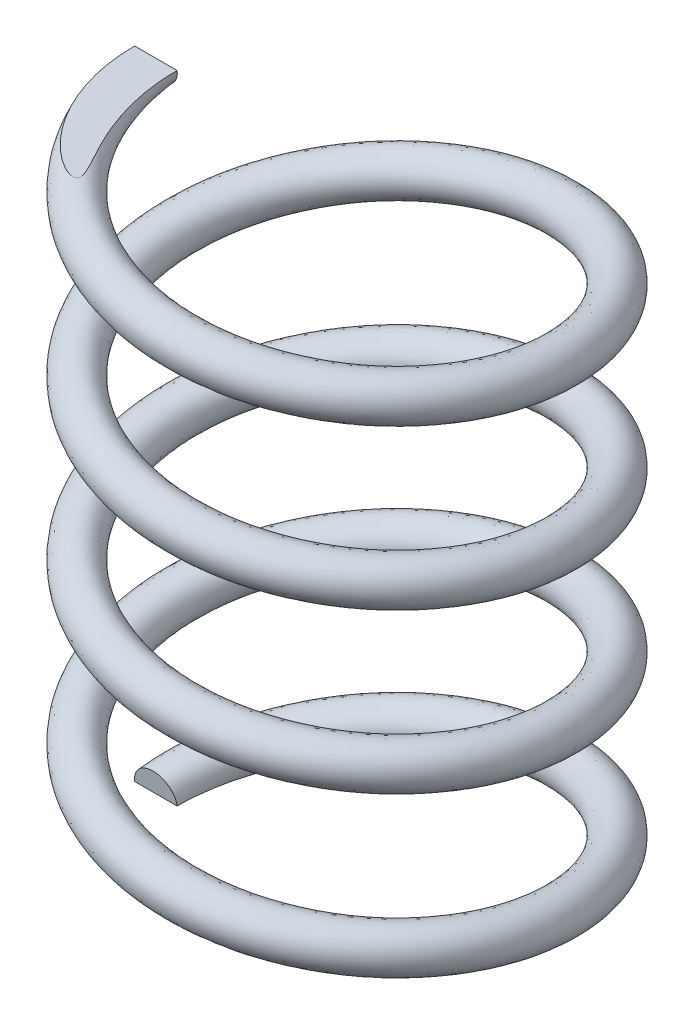
SolidWorks part; units mm, degrees
ref_plane "Front Plane" through (0, 0, 0) normal (0, 0, 1) x (1, 0, 0)
ref_plane "Top Plane" through (0, 0, 0) normal (0, 1, 0) x (1, 0, 0)
ref_plane "Right Plane" through (0, 0, 0) normal (1, 0, 0) x (0, 0, -1)
sketch "Sketch2" plane through (0, 0, 0) normal (0, 1, 0) x (1, 0, 0)
  circle A0 centre (0, 0) radius 4.5
  dimension "D1" = 9
curve "Helix/Spiral1" pitch 3.75 height 15 turns 4
sweep "Sweep1" add path "Helix/Spiral1" circular profile diameter 1 parameters "D3"=1
sketch "Sketch15" plane through (0, 0, 0) normal (1, 0, 0) x (0, 0, -1)
  line L0 (0, 0) -> (0, 15) construction
  line L1 (7.0278, 15) -> (-7.0278, 15)
  line L2 (-7.0278, 15) -> (-7.0278, 17.4892)
  line L3 (-7.0278, 17.4892) -> (7.0278, 17.4892)
  line L4 (7.0278, 17.4892) -> (7.0278, 15)
  line L5 (-7.0278, 0) -> (7.0278, 0)
  line L6 (7.0278, 0) -> (7.0278, -2.8144)
  line L7 (7.0278, -2.8144) -> (-7.0278, -2.8144)
  line L8 (-7.0278, -2.8144) -> (-7.0278, 0)
  point P6 (0, 15)
  point P11 (0, 0)
  dimension "D1" = 15
extrude "Cut-Extrude1" cut sketch "Sketch15" against normal mid plane 20
